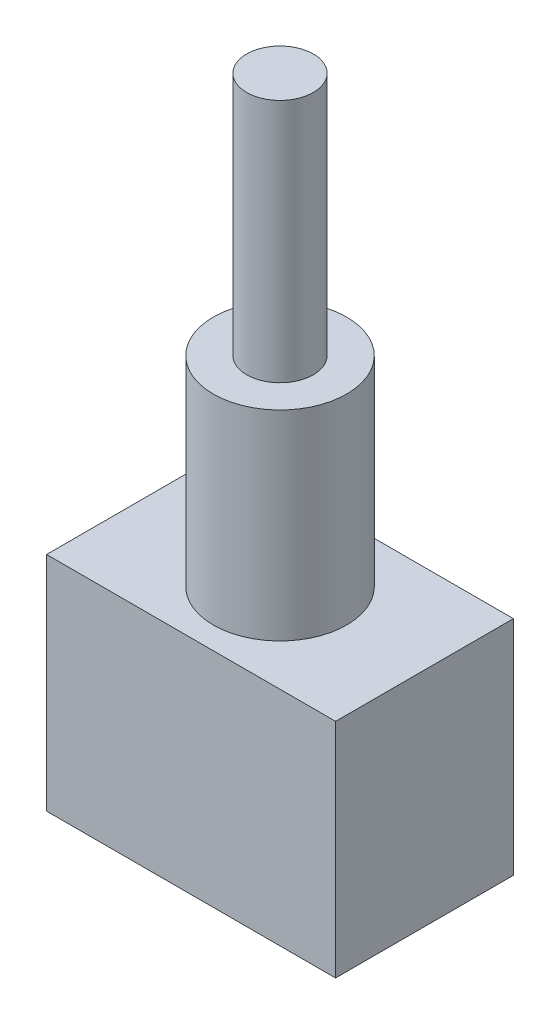
SolidWorks part; units mm, degrees
ref_plane "Front Plane" through (0, 0, 0) normal (0, 0, 1) x (1, 0, 0)
ref_plane "Top Plane" through (0, 0, 0) normal (0, 1, 0) x (1, 0, 0)
ref_plane "Right Plane" through (0, 0, 0) normal (1, 0, 0) x (0, 0, -1)
sketch "Sketch1" plane through (0, 0, 0) normal (0, 1, 0) x (1, 0, 0)
  line L1 (0, 0) -> (13, 0)
  line L2 (0, 0) -> (0, 8)
  line L3 (0, 8) -> (13, 8)
  line L4 (13, 0) -> (13, 8)
  dimension "D1" = 13
  dimension "D2" = 8
extrude "Boss-Extrude1" add sketch "Sketch1" along normal blind 10
sketch "Sketch2" plane through (0, 10, 0) normal (0, 1, 0) x (1, 0, 0)
  line L0 (13, 0) -> (13, 8) construction
  line L1 (13, 8) -> (0, 8) construction
  circle A0 centre (6.5, 4) radius 3
  point P2 (0, 0)
  point P5 (13, 4)
  point P8 (6.5, 8)
  dimension "D1" = 6
extrude "Boss-Extrude2" add sketch "Sketch2" along normal blind 9
sketch "Sketch3" plane through (0, 19, 0) normal (0, 1, 0) x (1, 0, 0)
  circle A0 centre (6.5, 4) radius 1.5
  dimension "D1" = 3
extrude "Boss-Extrude3" add sketch "Sketch3" along normal blind 11
